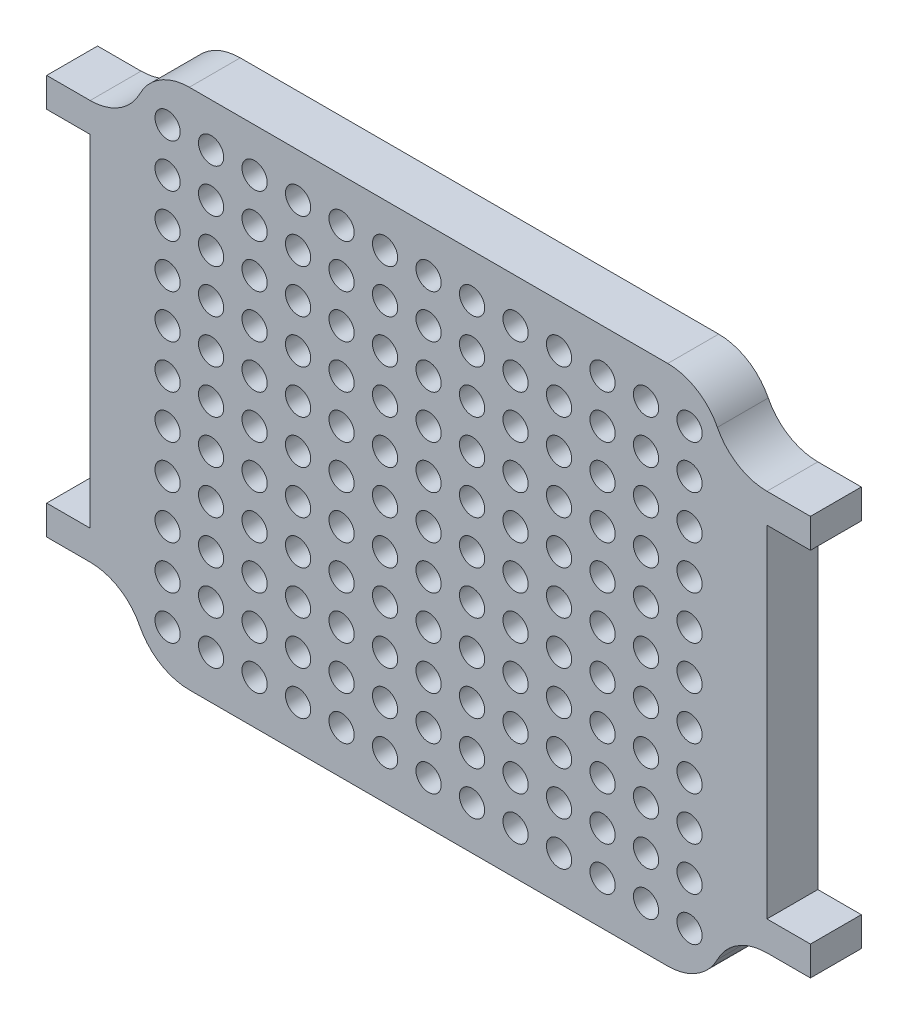
SolidWorks part; units mm, degrees
material "Acrylic (Medium-high impact)"
ref_plane "Front Plane" through (0, 0, 0) normal (0, 0, 1) x (1, 0, 0)
ref_plane "Top Plane" through (0, 0, 0) normal (0, 1, 0) x (1, 0, 0)
ref_plane "Right Plane" through (0, 0, 0) normal (1, 0, 0) x (0, 0, -1)
sketch "Sketch1" plane through (0, 0, 0) normal (0, 0, 1) x (1, 0, 0)
  line L0 (-1000, 0) -> (49000, 0) construction
  line L1 (0, -1000) -> (0, 49000) construction
  line L2 (-38.9, 19.6) -> (-38.9, -19.6)
  line L3 (-38.9, 19.6) -> (-43.9, 19.6)
  line L4 (-43.9, 19.6) -> (-43.9, 22.98)
  line L5 (-43.9, 22.98) -> (-38.9, 22.98)
  line L6 (-43.9, -22.98) -> (-38.9, -22.98)
  line L7 (-43.9, -19.6) -> (-43.9, -22.98)
  line L8 (-38.9, -19.6) -> (-43.9, -19.6)
  line L9 (-27.5, 30) -> (27.5, 30)
  line L10 (-38.9, 29.3632) -> (-27.5, 23.6168) construction
  line L11 (-27.5, -30) -> (27.5, -30)
  line L12 (43.9, -22.98) -> (38.9, -22.98)
  line L13 (43.9, -19.6) -> (43.9, -22.98)
  line L14 (38.9, -19.6) -> (43.9, -19.6)
  line L15 (38.9, 19.6) -> (38.9, -19.6)
  line L16 (38.9, 19.6) -> (43.9, 19.6)
  line L17 (43.9, 19.6) -> (43.9, 22.98)
  line L18 (43.9, 22.98) -> (38.9, 22.98)
  line L19 (-30, 25) -> (-25, 25) construction
  line L20 (-30, 25) -> (-30, 20) construction
  arc A0 (-38.9, 22.98) -> (-33.2, 26.49) centre (-38.9, 29.3632) ccw
  arc A1 (-33.2, 26.49) -> (-27.5, 30) centre (-27.5, 23.6168) cw
  arc A2 (-33.2, -26.49) -> (-27.5, -30) centre (-27.5, -23.6168) ccw
  arc A3 (-38.9, -22.98) -> (-33.2, -26.49) centre (-38.9, -29.3632) cw
  arc A4 (33.2, -26.49) -> (27.5, -30) centre (27.5, -23.6168) cw
  arc A5 (38.9, -22.98) -> (33.2, -26.49) centre (38.9, -29.3632) ccw
  arc A6 (38.9, 22.98) -> (33.2, 26.49) centre (38.9, 29.3632) cw
  arc A7 (33.2, 26.49) -> (27.5, 30) centre (27.5, 23.6168) ccw
  circle A8 centre (-30, 25) radius 1.45
  circle A9 centre (-25, 25) radius 1.45
  circle A10 centre (-20, 25) radius 1.45
  circle A11 centre (-15, 25) radius 1.45
  circle A12 centre (-10, 25) radius 1.45
  circle A13 centre (-5, 25) radius 1.45
  circle A14 centre (0, 25) radius 1.45
  circle A15 centre (5, 25) radius 1.45
  circle A16 centre (10, 25) radius 1.45
  circle A17 centre (15, 25) radius 1.45
  circle A18 centre (20, 25) radius 1.45
  circle A19 centre (25, 25) radius 1.45
  circle A20 centre (30, 25) radius 1.45
  circle A21 centre (-25, 20) radius 1.45
  circle A22 centre (-20, 20) radius 1.45
  circle A23 centre (-15, 20) radius 1.45
  circle A24 centre (-10, 20) radius 1.45
  circle A25 centre (-5, 20) radius 1.45
  circle A26 centre (0, 20) radius 1.45
  circle A27 centre (5, 20) radius 1.45
  circle A28 centre (10, 20) radius 1.45
  circle A29 centre (15, 20) radius 1.45
  circle A30 centre (20, 20) radius 1.45
  circle A31 centre (25, 20) radius 1.45
  circle A32 centre (30, 20) radius 1.45
  circle A33 centre (-25, 15) radius 1.45
  circle A34 centre (-20, 15) radius 1.45
  circle A35 centre (-15, 15) radius 1.45
  circle A36 centre (-10, 15) radius 1.45
  circle A37 centre (-5, 15) radius 1.45
  circle A38 centre (0, 15) radius 1.45
  circle A39 centre (5, 15) radius 1.45
  circle A40 centre (10, 15) radius 1.45
  circle A41 centre (15, 15) radius 1.45
  circle A42 centre (20, 15) radius 1.45
  circle A43 centre (25, 15) radius 1.45
  circle A44 centre (30, 15) radius 1.45
  circle A45 centre (-25, 10) radius 1.45
  circle A46 centre (-20, 10) radius 1.45
  circle A47 centre (-15, 10) radius 1.45
  circle A48 centre (-10, 10) radius 1.45
  circle A49 centre (-5, 10) radius 1.45
  circle A50 centre (0, 10) radius 1.45
  circle A51 centre (5, 10) radius 1.45
  circle A52 centre (10, 10) radius 1.45
  circle A53 centre (15, 10) radius 1.45
  circle A54 centre (20, 10) radius 1.45
  circle A55 centre (25, 10) radius 1.45
  circle A56 centre (30, 10) radius 1.45
  circle A57 centre (-25, 5) radius 1.45
  circle A58 centre (-20, 5) radius 1.45
  circle A59 centre (-15, 5) radius 1.45
  circle A60 centre (-10, 5) radius 1.45
  circle A61 centre (-5, 5) radius 1.45
  circle A62 centre (0, 5) radius 1.45
  circle A63 centre (5, 5) radius 1.45
  circle A64 centre (10, 5) radius 1.45
  circle A65 centre (15, 5) radius 1.45
  circle A66 centre (20, 5) radius 1.45
  circle A67 centre (25, 5) radius 1.45
  circle A68 centre (30, 5) radius 1.45
  circle A69 centre (-25, 0) radius 1.45
  circle A70 centre (-20, 0) radius 1.45
  circle A71 centre (-15, 0) radius 1.45
  circle A72 centre (-10, 0) radius 1.45
  circle A73 centre (-5, 0) radius 1.45
  circle A74 centre (0, 0) radius 1.45
  circle A75 centre (5, 0) radius 1.45
  circle A76 centre (10, 0) radius 1.45
  circle A77 centre (15, 0) radius 1.45
  circle A78 centre (20, 0) radius 1.45
  circle A79 centre (25, 0) radius 1.45
  circle A80 centre (30, 0) radius 1.45
  circle A81 centre (-25, -5) radius 1.45
  circle A82 centre (-20, -5) radius 1.45
  circle A83 centre (-15, -5) radius 1.45
  circle A84 centre (-10, -5) radius 1.45
  circle A85 centre (-5, -5) radius 1.45
  circle A86 centre (0, -5) radius 1.45
  circle A87 centre (5, -5) radius 1.45
  circle A88 centre (10, -5) radius 1.45
  circle A89 centre (15, -5) radius 1.45
  circle A90 centre (20, -5) radius 1.45
  circle A91 centre (25, -5) radius 1.45
  circle A92 centre (30, -5) radius 1.45
  circle A93 centre (-25, -10) radius 1.45
  circle A94 centre (-20, -10) radius 1.45
  circle A95 centre (-15, -10) radius 1.45
  circle A96 centre (-10, -10) radius 1.45
  circle A97 centre (-5, -10) radius 1.45
  circle A98 centre (0, -10) radius 1.45
  circle A99 centre (5, -10) radius 1.45
  circle A100 centre (10, -10) radius 1.45
  circle A101 centre (15, -10) radius 1.45
  circle A102 centre (20, -10) radius 1.45
  circle A103 centre (25, -10) radius 1.45
  circle A104 centre (30, -10) radius 1.45
  circle A105 centre (-25, -15) radius 1.45
  circle A106 centre (-20, -15) radius 1.45
  circle A107 centre (-15, -15) radius 1.45
  circle A108 centre (-10, -15) radius 1.45
  circle A109 centre (-5, -15) radius 1.45
  circle A110 centre (0, -15) radius 1.45
  circle A111 centre (5, -15) radius 1.45
  circle A112 centre (10, -15) radius 1.45
  circle A113 centre (15, -15) radius 1.45
  circle A114 centre (20, -15) radius 1.45
  circle A115 centre (25, -15) radius 1.45
  circle A116 centre (30, -15) radius 1.45
  circle A117 centre (-25, -20) radius 1.45
  circle A118 centre (-20, -20) radius 1.45
  circle A119 centre (-15, -20) radius 1.45
  circle A120 centre (-10, -20) radius 1.45
  circle A121 centre (-5, -20) radius 1.45
  circle A122 centre (0, -20) radius 1.45
  circle A123 centre (5, -20) radius 1.45
  circle A124 centre (10, -20) radius 1.45
  circle A125 centre (15, -20) radius 1.45
  circle A126 centre (20, -20) radius 1.45
  circle A127 centre (25, -20) radius 1.45
  circle A128 centre (30, -20) radius 1.45
  circle A129 centre (-25, -25) radius 1.45
  circle A130 centre (-20, -25) radius 1.45
  circle A131 centre (-15, -25) radius 1.45
  circle A132 centre (-10, -25) radius 1.45
  circle A133 centre (-5, -25) radius 1.45
  circle A134 centre (0, -25) radius 1.45
  circle A135 centre (5, -25) radius 1.45
  circle A136 centre (10, -25) radius 1.45
  circle A137 centre (15, -25) radius 1.45
  circle A138 centre (20, -25) radius 1.45
  circle A139 centre (25, -25) radius 1.45
  circle A140 centre (30, -25) radius 1.45
  circle A141 centre (-30, 20) radius 1.45
  circle A142 centre (-30, 15) radius 1.45
  circle A143 centre (-30, 10) radius 1.45
  circle A144 centre (-30, 5) radius 1.45
  circle A145 centre (-30, 0) radius 1.45
  circle A146 centre (-30, -5) radius 1.45
  circle A147 centre (-30, -10) radius 1.45
  circle A148 centre (-30, -15) radius 1.45
  circle A149 centre (-30, -20) radius 1.45
  circle A150 centre (-30, -25) radius 1.45
  point P4 (-38.9, 0)
  point P16 (0, 30)
  point P17 (-33.2, 26.49)
  dimension "D7" = 2.9
  dimension "D1" = 30
  dimension "D2" = 39.2
  dimension "D3" = 3.38
  dimension "D4" = 5
  dimension "D5" = 38.9
  dimension "D6" = 55
  dimension "D8" = 30
  dimension "D9" = 25
  dimension "D10" = 13
  dimension "D12" = 5
  dimension "D13" = 5
  dimension "D11" = 11
extrude "Boss-Extrude1" add sketch "Sketch1" along normal blind 5.85
